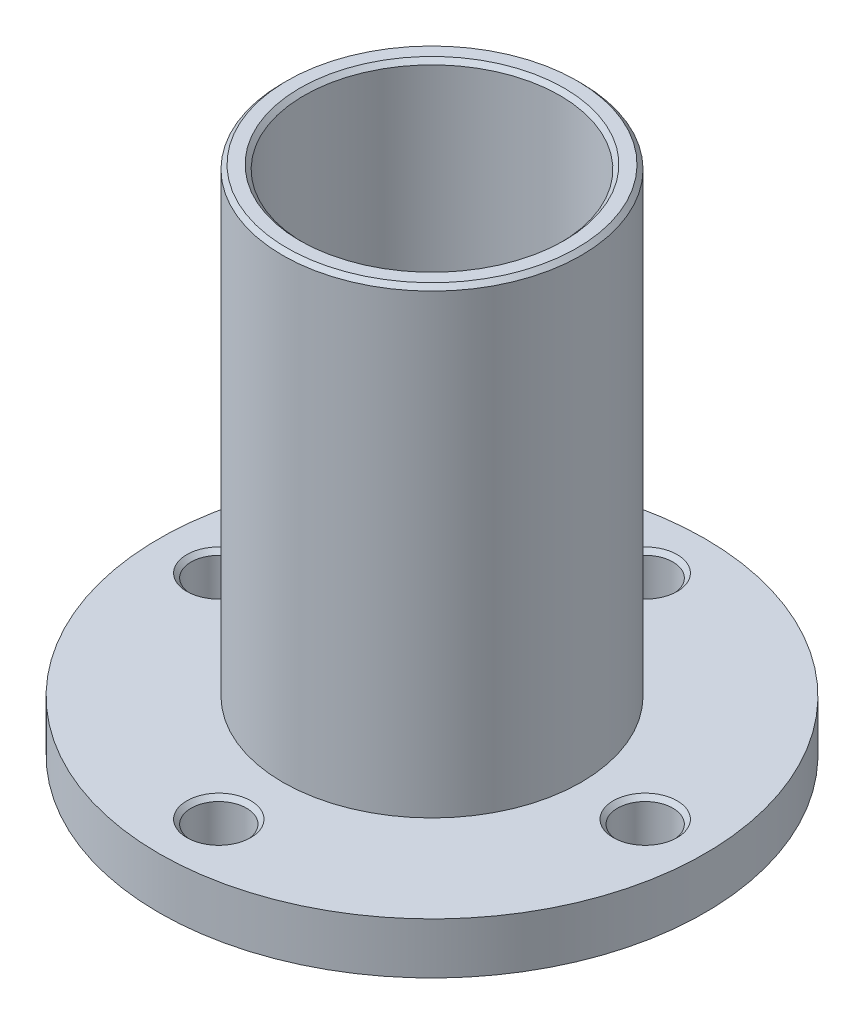
SolidWorks part; units mm, degrees
ref_plane "Front Plane" through (0, 0, 0) normal (0, 0, 1) x (1, 0, 0)
ref_plane "Top Plane" through (0, 0, 0) normal (0, 1, 0) x (1, 0, 0)
ref_plane "Right Plane" through (0, 0, 0) normal (1, 0, 0) x (0, 0, -1)
sketch "Sketch1" plane through (0, 0, 0) normal (0, 0, 1) x (1, 0, 0)
  line L0 (0, 0) -> (0, 58.576) construction
  line L1 (-15, 2.3) -> (-15, 60)
  line L2 (-15, 60) -> (-17.5, 60)
  line L3 (-17.5, 60) -> (-17.5, 6)
  line L4 (-17.5, 6) -> (-32, 6)
  line L5 (-32, 6) -> (-32, 0)
  line L6 (-32, 0) -> (-20, 0)
  line L7 (-15, 2.3) -> (-20, 2.3)
  line L8 (-20, 2.3) -> (-20, 0)
  dimension "D1" = 30
  dimension "D2" = 35
  dimension "D3" = 60
  dimension "D4" = 6
  dimension "D5" = 64
  dimension "D6" = 2.3
  dimension "D7" = 40
revolve "Revolve1" add sketch "Sketch1" angle 360 about L0
chamfer "Chamfer1" distance 0.5 angle 45 2 edges at (0, 60, -15) (0, 60, -17.5)
sketch "Sketch2" plane through (0, 6, 0) normal (0, 1, 0) x (1, 0, 0)
  line L0 (0, 35.1605) -> (0, -35.1605) construction
  line L1 (39.8713, 0) -> (-39.8713, 0) construction
  line L2 (0, 0) -> (0, 25) construction
  circle A0 centre (0, 0) radius 25 construction
  circle A1 centre (0, 25) radius 3.25
  circle A2 centre (25, 0) radius 3.25
  circle A3 centre (0, -25) radius 3.25
  circle A4 centre (-25, 0) radius 3.25
  point P6 (0, 0)
  point P9 (0, 0)
  dimension "D1" = 50
  dimension "D2" = 6.5
  dimension "D3" = 4
extrude "Cut-Extrude1" cut sketch "Sketch2" against normal through all
chamfer "Chamfer2" distance 0.5 angle 45 8 edges at (0, 6, 28.25) (-25, 6, 3.25) (25, 6, 3.25) (0, 6, -21.75) (0, 0, 28.25) (-25, 0, 3.25) (0, 0, -21.75) (25, 0, 3.25)
chamfer "Chamfer3" distance 0.5 angle 45 1 edges at (0, 2.3, -15)
